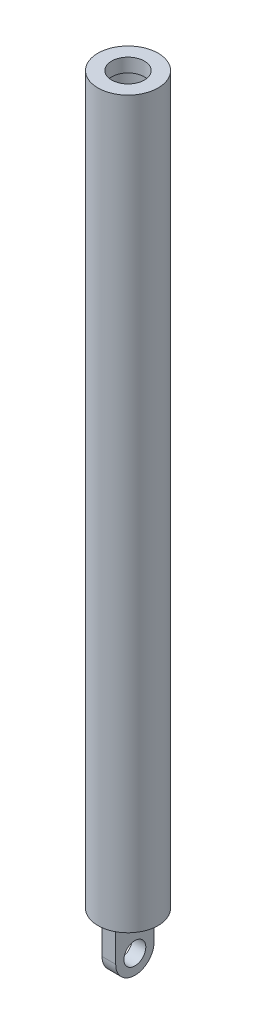
SolidWorks part; units mm, degrees
ref_plane "前基準面" through (0, 0, 0) normal (0, 0, 1) x (1, 0, 0)
ref_plane "上基準面" through (0, 0, 0) normal (0, 1, 0) x (1, 0, 0)
ref_plane "右基準面" through (0, 0, 0) normal (1, 0, 0) x (0, 0, -1)
sketch "草圖1" plane through (0, 0, 0) normal (0, 1, 0) x (1, 0, 0)
  circle A0 centre (0, 0) radius 11
  circle A1 centre (0, 0) radius 9
  dimension "D1" = 22
  dimension "D2" = 18
extrude "填料-伸長1" add sketch "草圖1" along normal blind 248
sketch "草圖2" plane through (0, 0, 0) normal (0, -1, 0) x (1, 0, 0)
  circle A0 centre (0, 0) radius 11 construction
  circle A1 centre (0, 0) radius 11
extrude "填料-伸長2" add sketch "草圖2" along normal blind 12
sketch "草圖4" plane through (0, 0, 0) normal (1, 0, 0) x (0, 0, -1)
  line L0 (-7, -12) -> (-7, -25)
  line L1 (-11, -12) -> (11, -12) construction
  line L2 (7, -12) -> (7, -25)
  line L3 (-7, -12) -> (7, -12)
  arc A0 (-7, -25) -> (7, -25) centre (0, -25) ccw
  circle A1 centre (0, -25) radius 4
  dimension "D1" = 14
  dimension "D3" = 8
  dimension "D2" = 13
extrude "填料-伸長4" add sketch "草圖4" along normal mid plane 5
sketch "草圖5" plane through (0, 248, 0) normal (0, 1, 0) x (1, 0, 0)
  circle A0 centre (0, 0) radius 6
  circle A1 centre (0, 0) radius 11
  circle A2 centre (0, 0) radius 11
  dimension "D2" = 12
  dimension "D1" = 0
extrude "填料-伸長5" add sketch "草圖5" along normal blind 5
